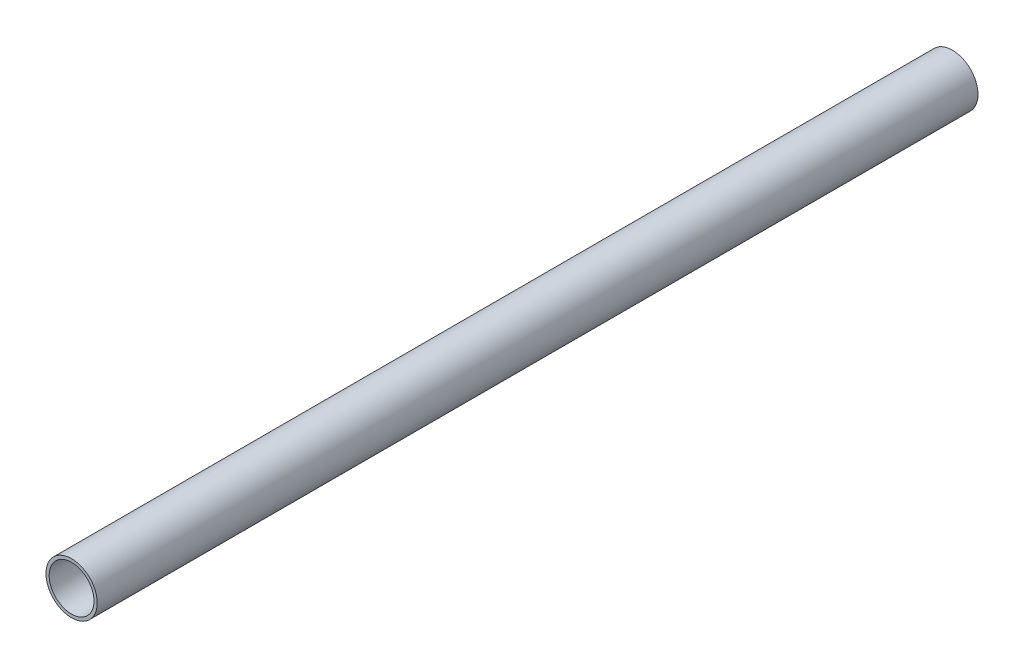
SolidWorks part; units mm, degrees
material "Thornel Mat VMA"
ref_plane "Front Plane" through (0, 0, 0) normal (0, 0, 1) x (1, 0, 0)
ref_plane "Top Plane" through (0, 0, 0) normal (0, 1, 0) x (1, 0, 0)
ref_plane "Right Plane" through (0, 0, 0) normal (1, 0, 0) x (0, 0, -1)
sketch "Sketch1" plane through (0, 0, 0) normal (0, 0, 1) x (1, 0, 0)
  circle A0 centre (0, 0) radius 8
ref_plane "Plane1" through (0, 0, 275) normal (0, 0, 1) x (1, 0, 0)
sketch "Sketch2" plane through (0, 0, 275) normal (0, 0, 1) x (1, 0, 0)
  circle A0 centre (0, 0) radius 8
loft "Loft1" add profiles "Sketch1", "Sketch2"
sketch "Sketch3" plane through (0, 0, 0) normal (0, 0, 1) x (1, 0, 0)
  circle A0 centre (0, 0) radius 7
extrude "Cut-Extrude1" cut sketch "Sketch3" against normal through all both and the other way through all
